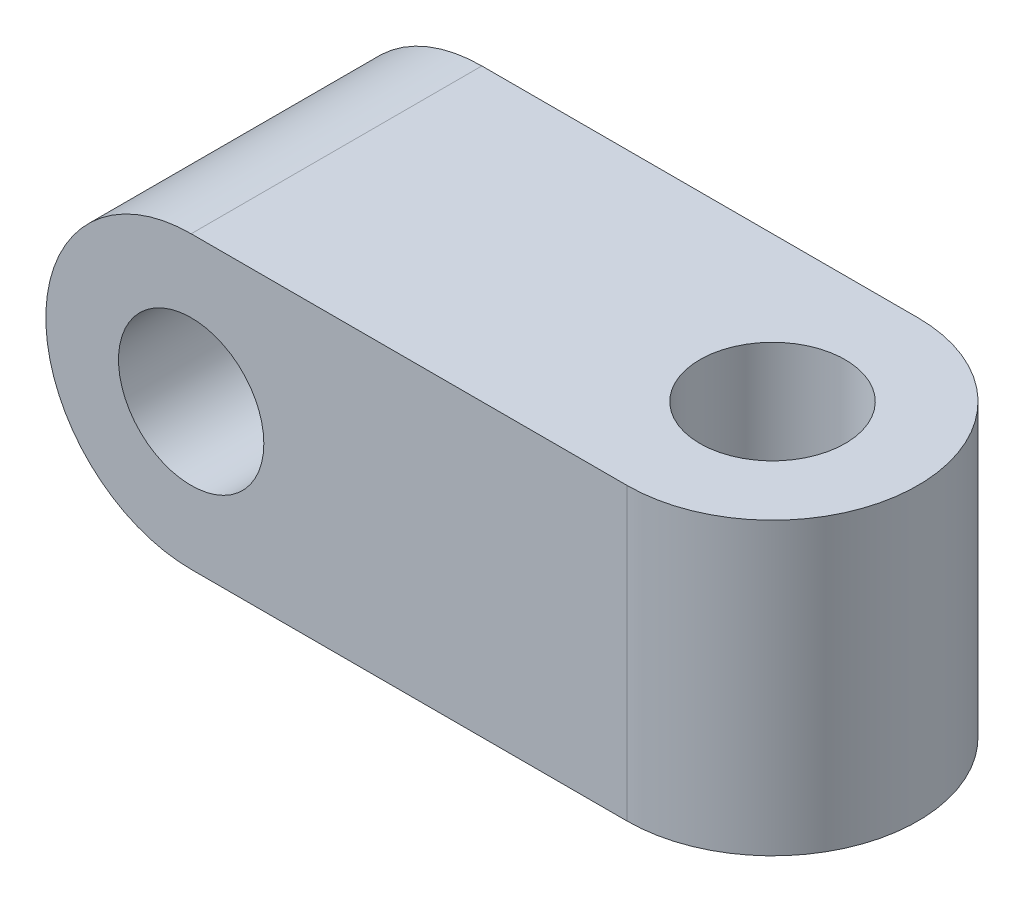
SolidWorks part; units mm, degrees
ref_plane "Front Plane" through (0, 0, 0) normal (0, 0, 1) x (1, 0, 0)
ref_plane "Top Plane" through (0, 0, 0) normal (0, 1, 0) x (1, 0, 0)
ref_plane "Right Plane" through (0, 0, 0) normal (1, 0, 0) x (0, 0, -1)
sketch "Sketch1" plane through (0, 0, 0) normal (0, 0, 1) x (1, 0, 0)
  circle A0 centre (0, 0) radius 2
extrude "Boss-Extrude1" add sketch "Sketch1" along normal blind 4
sketch "Sketch2" plane through (0, 0, 4) normal (0, 0, 1) x (1, 0, 0)
  line L0 (0, 2) -> (3, 2)
  line L1 (3, 2) -> (3, -2)
  line L2 (3, -2) -> (0, -2)
  circle A0 centre (0, 0) radius 2
  arc A1 (0, 2) -> (0, -2) centre (0, 0) cw
  circle M3 centre (0, 0) radius 2
  dimension "D1" = 4
  dimension "D2" = 3
extrude "Boss-Extrude2" add sketch "Sketch2" against normal blind 4 contours L2 L1 L0 M3
sketch "Sketch3" plane through (0, 0, 4) normal (0, 0, 1) x (1, 0, 0)
  circle A0 centre (0, 0) radius 1
extrude "Cut-Extrude1" cut sketch "Sketch3" against normal through all
ref_plane "Plane1" through (0, 0, 0) normal (0, 1, 0) x (1, 0, 0)
sketch "Sketch7" plane through (0, 0, 0) normal (0, 1, 0) x (1, 0, 0)
  line L4 (3, 0) -> (3, -4)
  line L5 (3, -4) -> (6, -4)
  line L7 (6, 0) -> (3, 0)
  arc A0 (6, 0) -> (6, -4) centre (6, -2) cw
  circle A1 centre (6, -2) radius 1
  dimension "D3" = 2
  dimension "D4" = 2
  dimension "D5" = 2
  dimension "D6" = 2
  dimension "D1" = 3
  dimension "D2" = 3
  dimension "D7" = 3
extrude "Boss-Extrude4" add sketch "Sketch7" along normal mid plane 4
